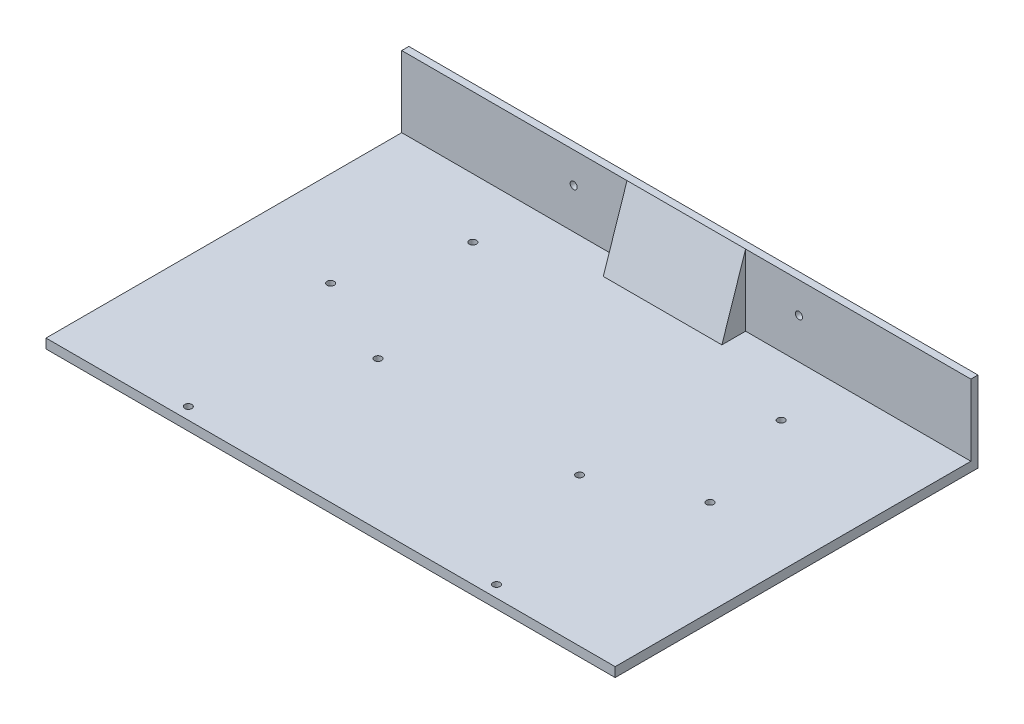
SolidWorks part; units mm, degrees
ref_plane "Front Plane" through (0, 0, 0) normal (0, 0, 1) x (1, 0, 0)
ref_plane "Top Plane" through (0, 0, 0) normal (0, 1, 0) x (1, 0, 0)
ref_plane "Right Plane" through (0, 0, 0) normal (1, 0, 0) x (0, 0, -1)
sketch "Sketch1" plane through (0, 0, 0) normal (0, 1, 0) x (1, 0, 0)
  line L1 (-120, 75) -> (120, 75)
  line L2 (-120, 75) -> (-120, -75)
  line L3 (-120, -75) -> (120, -75)
  line L4 (120, 75) -> (120, -75)
  line L5 (-120, 75) -> (120, -75) construction
  line L6 (-120, -75) -> (120, 75) construction
  point P0 (0, 0)
  dimension "D1" = 150
  dimension "D2" = 240
extrude "Boss-Extrude1" add sketch "Sketch1" along normal blind 4
sketch "Sketch2" plane through (0, 0, 0) normal (0, -1, 0) x (1, 0, 0)
  line L0 (-120, -75) -> (-120, 75) construction
  line L1 (120, 75) -> (120, -75) construction
  circle A0 centre (80, -5) radius 32.5 construction
  circle A1 centre (-80, -5) radius 32.5 construction
  circle A2 centre (80, -5) radius 1.5
  circle A3 centre (-80, -5) radius 1.5
  dimension "D1" = 65
  dimension "D2" = 40
  dimension "D3" = 40
  dimension "D5" = 3
  dimension "D4" = 5
sketch "Sketch3" plane through (0, 4, 0) normal (0, 1, 0) x (1, 0, 0)
  line L0 (-120, -75) -> (120, -75) construction
  line L1 (-65, 50) -> (65, 50) construction
  line L2 (-65, 50) -> (-65, -70) construction
  line L3 (-65, -70) -> (65, -70) construction
  line L4 (65, 50) -> (65, -70) construction
  line L5 (-65, 50) -> (65, -70) construction
  line L6 (-65, -70) -> (65, 50) construction
  circle A0 centre (-65, 50) radius 1.5
  circle A1 centre (65, 50) radius 1.5
  circle A2 centre (65, -70) radius 1.5
  circle A3 centre (-65, -70) radius 1.5
  point P0 (0, -10)
  dimension "D1" = 3
  dimension "D4" = 5
  dimension "D2" = 130
  dimension "D3" = 120
extrude "Cut-Extrude1" cut sketch "Sketch3" against normal blind 50
sketch "Sketch4" plane through (0, 4, 0) normal (0, 1, 0) x (1, 0, 0)
  line L0 (-42.5, -12.5) -> (42.5, -12.5) construction
  line L1 (-120, -75) -> (120, -75) construction
  line L2 (-56, -71) -> (56, -71) construction
  line L3 (-56, -71) -> (-56, 46) construction
  line L4 (-56, 46) -> (56, 46) construction
  line L5 (56, -71) -> (56, 46) construction
  line L6 (-56, -71) -> (56, 46) construction
  line L7 (-56, 46) -> (56, -71) construction
  circle A0 centre (42.5, -12.5) radius 1.5
  circle A1 centre (-42.5, -12.5) radius 1.5
  point P3 (0, -12.5)
  point P6 (0, -12.5)
  dimension "D2" = 3
  dimension "D1" = 85
  dimension "D3" = 117
  dimension "D4" = 112
  dimension "D5" = 4
sketch "Sketch5" plane through (0, 0, -75) normal (0, 0, -1) x (-1, 0, 0)
  line L0 (-120, 0) -> (120, 0) construction
  line L1 (-120, 0) -> (120, 0)
  line L2 (-120, 0) -> (-120, 34)
  line L3 (-120, 34) -> (120, 34)
  line L4 (120, 0) -> (120, 34)
  line L5 (-120, 4) -> (120, 4) construction
  line L6 (-47.5, 21) -> (47.5, 21) construction
  circle A0 centre (47.5, 21) radius 1.5
  circle A1 centre (-47.5, 21) radius 1.5
  point P6 (0, 34)
  point P13 (0, 21)
  dimension "D3" = 3
  dimension "D1" = 30
  dimension "D4" = 95
  dimension "D5" = 13
extrude "Boss-Extrude4" add sketch "Sketch5" along normal blind 3
sketch "Sketch8" plane through (0, 0, 0) normal (1, 0, 0) x (0, 0, -1)
  line L0 (75, 34) -> (65, 4)
  line L1 (-75, 4) -> (75, 4) construction
  line L2 (75, 34) -> (75, 4) construction
  line L3 (75, 34) -> (75, 4)
  line L4 (75, 4) -> (65, 4)
  dimension "D1" = 10
extrude "Boss-Extrude5" add sketch "Sketch8" along normal mid plane 50
extrude "Cut-Extrude2" cut sketch "Sketch4" against normal through all
extrude "Cut-Extrude3" cut sketch "Sketch2" against normal blind 10
